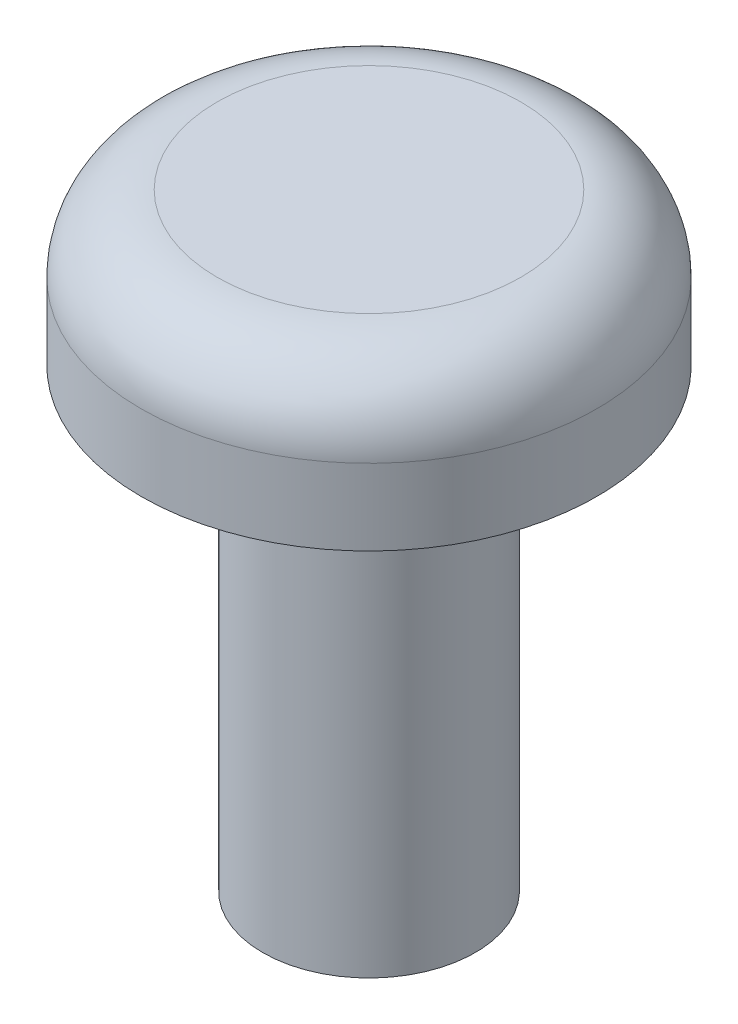
SolidWorks part; units mm, degrees
ref_plane "Front Plane" through (0, 0, 0) normal (0, 0, 1) x (1, 0, 0)
ref_plane "Top Plane" through (0, 0, 0) normal (0, 1, 0) x (1, 0, 0)
ref_plane "Right Plane" through (0, 0, 0) normal (1, 0, 0) x (0, 0, -1)
sketch "Sketch1" plane through (0, 0, 0) normal (0, 1, 0) x (1, 0, 0)
  circle A0 centre (0, 0) radius 1.4
  dimension "D1" = 2.8
extrude "Boss-Extrude1" add sketch "Sketch1" along normal blind 6
sketch "Sketch2" plane through (0, 6, 0) normal (0, 1, 0) x (1, 0, 0)
  circle A0 centre (0, 0) radius 3
  dimension "D1" = 6
extrude "Boss-Extrude2" add sketch "Sketch2" along normal blind 2
fillet "Fillet1" radius 1 1 edges at (0, 8, 3)
